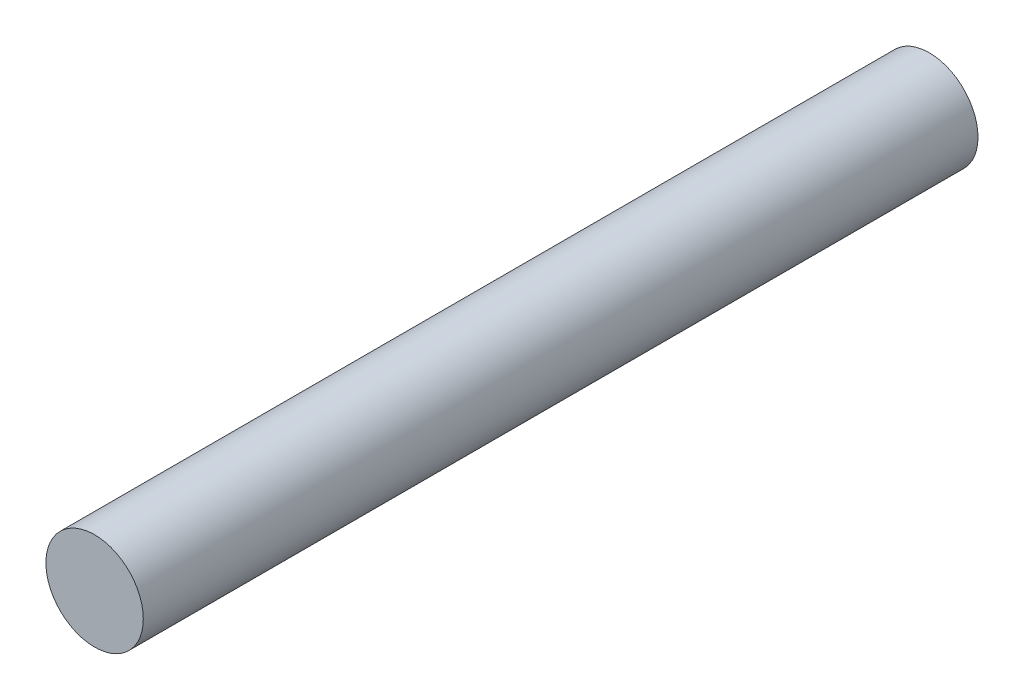
SolidWorks part; units mm, degrees
ref_plane "Front Plane" through (0, 0, 0) normal (0, 0, 1) x (1, 0, 0)
ref_plane "Top Plane" through (0, 0, 0) normal (0, 1, 0) x (1, 0, 0)
ref_plane "Right Plane" through (0, 0, 0) normal (1, 0, 0) x (0, 0, -1)
sketch "Sketch1" plane through (0, 0, 0) normal (0, 0, 1) x (1, 0, 0)
  circle A0 centre (0, 0) radius 3.5
extrude "Boss-Extrude1" add sketch "Sketch1" along normal mid plane 60
